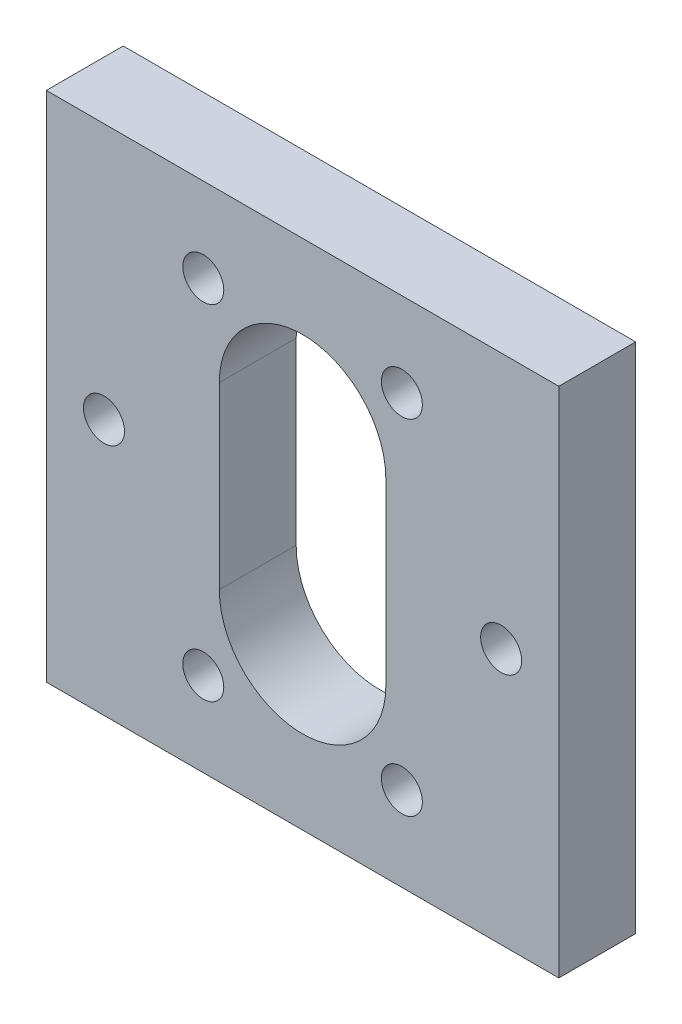
SolidWorks part; units mm, degrees
material "5052-O"
ref_plane "前基準面" through (0, 0, 0) normal (0, 0, 1) x (1, 0, 0)
ref_plane "上基準面" through (0, 0, 0) normal (0, 1, 0) x (1, 0, 0)
ref_plane "右基準面" through (0, 0, 0) normal (1, 0, 0) x (0, 0, -1)
sketch "草圖1" plane through (0, 0, 0) normal (0, 0, 1) x (1, 0, 0)
  line L1 (-20, -20) -> (20, -20)
  line L2 (-20, -20) -> (-20, 20)
  line L3 (-20, 20) -> (20, 20)
  line L4 (20, -20) -> (20, 20)
  line L5 (-20, -20) -> (20, 20) construction
  line L6 (-20, 20) -> (20, -20) construction
  point P0 (0, 0)
  dimension "D1" = 40
extrude "填料-伸長1" add sketch "草圖1" along normal blind 6
sketch "草圖2" plane through (0, 0, 6) normal (0, 0, 1) x (1, 0, 0)
  line L0 (0, -7) -> (0, 7) construction
  line L1 (-6.5, -7) -> (-6.5, 7)
  line L2 (6.5, -7) -> (6.5, 7)
  arc A0 (-6.5, -7) -> (6.5, -7) centre (0, -7) ccw
  arc A1 (6.5, 7) -> (-6.5, 7) centre (0, 7) ccw
  point P4 (0, 0)
  dimension "D2" = 6.5
  dimension "D1" = 14
extrude "除料-伸長1" cut sketch "草圖2" against normal through all and the other way through all
sketch "草圖3" plane through (0, 0, 6) normal (0, 0, 1) x (1, 0, 0)
  line L1 (6.5, -7) -> (6.5, 7) construction
  circle A0 centre (-15.5, 0) radius 1.6
  circle A1 centre (0, 0) radius 6.5 construction
  circle A2 centre (0, 0) radius 6.5 construction
  circle A3 centre (-7.75, 13.4234) radius 1.6
  circle A4 centre (0, 0) radius 6.5 construction
  circle A5 centre (7.75, 13.4234) radius 1.6
  circle A6 centre (0, 0) radius 6.5 construction
  circle A7 centre (15.5, 0) radius 1.6
  circle A8 centre (0, 0) radius 6.5 construction
  circle A9 centre (7.75, -13.4234) radius 1.6
  circle A10 centre (0, 0) radius 6.5 construction
  circle A11 centre (-7.75, -13.4234) radius 1.6
  point P24 (0, 0)
  dimension "D1" = 3.2
  dimension "D2" = 15.5
  dimension "D3" = 6
extrude "除料-伸長2" cut sketch "草圖3" against normal through all
